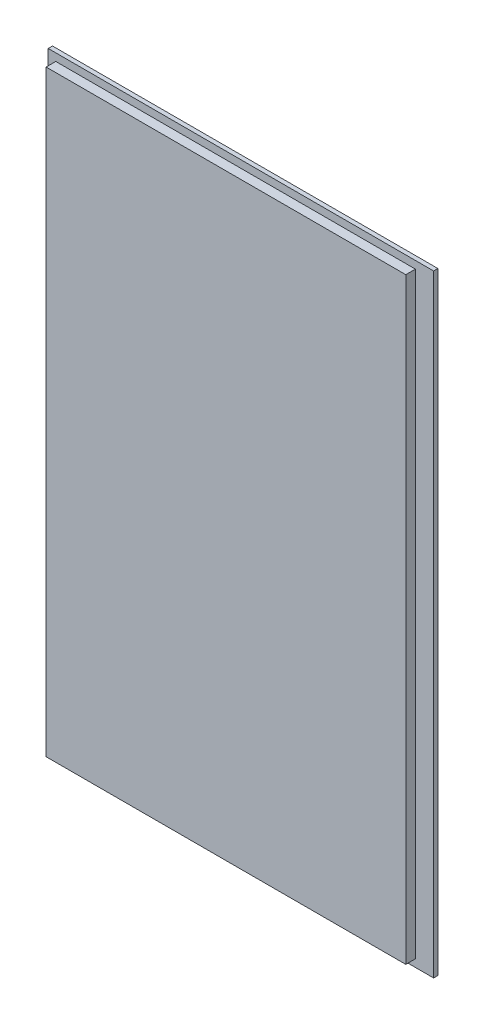
SolidWorks part; units mm, degrees
ref_plane "Přední rovina" through (0, 0, 0) normal (0, 0, 1) x (1, 0, 0)
ref_plane "Horní rovina" through (0, 0, 0) normal (0, 1, 0) x (1, 0, 0)
ref_plane "Pravá rovina" through (0, 0, 0) normal (1, 0, 0) x (0, 0, -1)
sketch "Skica1" plane through (0, 0, 0) normal (0, 0, 1) x (1, 0, 0)
  line L1 (0, 0) -> (72, 0)
  line L2 (0, 0) -> (0, 114.4)
  line L3 (0, 114.4) -> (72, 114.4)
  line L4 (72, 0) -> (72, 114.4)
  dimension "D1" = 114.4
  dimension "D2" = 72
extrude "Přidat vysunutím1" add sketch "Skica1" along normal blind 0.8
sketch "Skica2" plane through (0, 0, 0.8) normal (0, 0, 1) x (1, 0, 0)
  line L1 (1.4, 113) -> (68.6, 113)
  line L6 (1.4, 113) -> (1.4, 1.4)
  line L14 (0, 114.4) -> (0, 0) construction
  line L16 (1.4, 1.4) -> (68.6, 1.4)
  line L17 (68.6, 1.4) -> (68.6, 113)
  line L18 (72, 0) -> (72, 114.4) construction
  line L21 (72, 114.4) -> (0, 114.4) construction
  line L22 (0, 0) -> (72, 0) construction
  dimension "D1" = 1.4
  dimension "D2" = 3.4
  dimension "D3" = 1.4
  dimension "D4" = 1.4
extrude "Přidat vysunutím2" add sketch "Skica2" along normal blind 1.8
